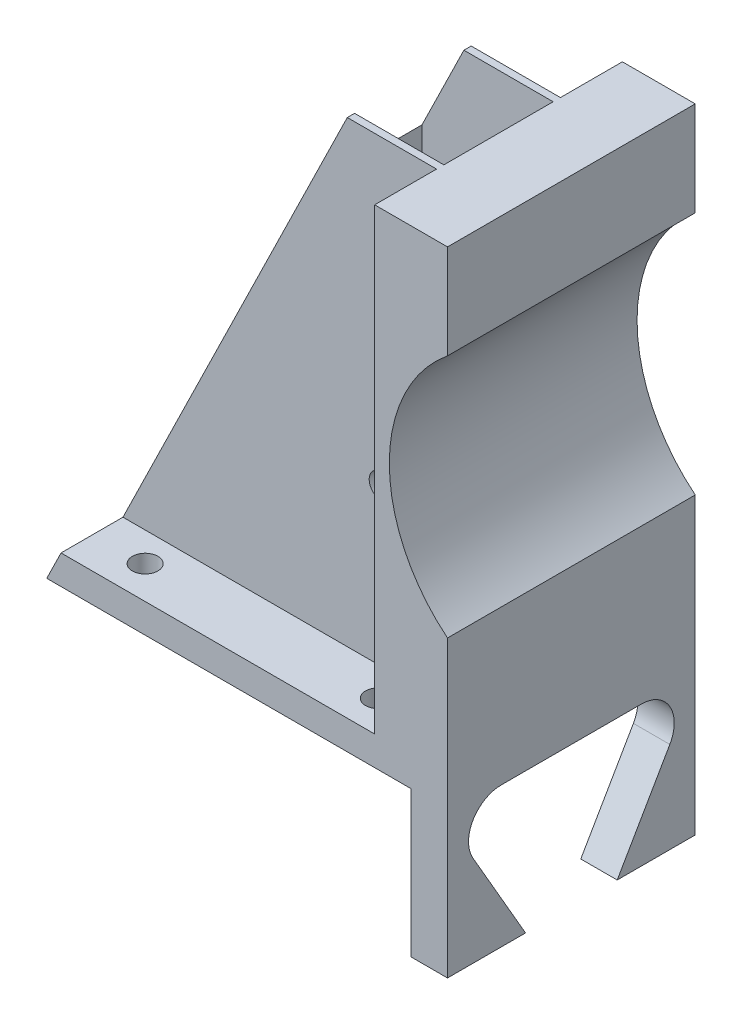
SolidWorks part; units mm, degrees
ref_plane "Front Plane" through (0, 0, 0) normal (0, 0, 1) x (1, 0, 0)
ref_plane "Top Plane" through (0, 0, 0) normal (0, 1, 0) x (1, 0, 0)
ref_plane "Right Plane" through (0, 0, 0) normal (1, 0, 0) x (0, 0, -1)
sketch "Sketch4" plane through (0, 0, 0) normal (0, 0, 1) x (1, 0, 0)
  line L0 (-25, -10) -> (30, -10)
  line L1 (-25, -10) -> (25, -10) construction
  line L2 (-25, -10) -> (-25, 10) construction
  line L3 (-25, 10) -> (25, 10) construction
  line L4 (25, -10) -> (25, 10) construction
  line L5 (-25, -10) -> (25, 10) construction
  line L6 (-25, 10) -> (25, -10) construction
  line L7 (30, -10) -> (30, 30.414)
  line L8 (30, 63.942) -> (30, 76.896)
  line L9 (30, 76.896) -> (7.7472, 76.896)
  line L10 (7.7472, 76.896) -> (-25, 10)
  line L11 (-25, 10) -> (-25, -10)
  arc A0 (30, 63.942) -> (30, 30.414) centre (43.605, 47.178) ccw
  point P0 (0, 0)
  dimension "D3" = 21.59
  dimension "D4" = 12.954
  dimension "D1" = 50
  dimension "D2" = 20
  dimension "D5" = 33.528
  dimension "D6" = 5
extrude "Boss-Extrude2" add sketch "Sketch4" along normal blind 34
sketch "Sketch5" plane through (0, 0, 34) normal (0, 0, 1) x (1, 0, 0)
  line L0 (-23.0419, 14) -> (7.7472, 76.896)
  line L1 (-25, -10) -> (25, -10)
  line L2 (-25, -10) -> (-25, 10)
  line L3 (-25, 10) -> (25, 10)
  line L4 (25, -10) -> (25, 10)
  line L5 (7.7472, 76.896) -> (-25, 10) construction
  line L6 (7.7472, 76.896) -> (20, 76.896)
  line L7 (30, 76.896) -> (7.7472, 76.896) construction
  line L8 (20, 76.896) -> (20, 14)
  line L9 (20, 14) -> (-23.0419, 14)
  dimension "D1" = 50
  dimension "D2" = 20
  dimension "D3" = 4
  dimension "D4" = 45
extrude "Cut-Extrude1" cut sketch "Sketch5" against normal blind 8.5
sketch "Sketch6" plane through (0, 0, 0) normal (0, 0, -1) x (-1, 0, 0)
  line L0 (23.0419, 14) -> (-20, 14)
  line L1 (25, -10) -> (-25, -10)
  line L2 (25, -10) -> (25, 10)
  line L3 (25, 10) -> (-25, 10)
  line L4 (-25, -10) -> (-25, 10)
  line L5 (-7.7472, 76.896) -> (25, 10) construction
  line L6 (-20, 14) -> (-20, 76.896)
  line L7 (-30, 76.896) -> (-7.7472, 76.896) construction
  line L8 (-20, 76.896) -> (-7.7472, 76.896)
  line L9 (-7.7472, 76.896) -> (23.0419, 14)
  dimension "D1" = 50
  dimension "D2" = 20
  dimension "D3" = 45
  dimension "D4" = 4
extrude "Cut-Extrude2" cut sketch "Sketch6" against normal blind 8.5
sketch "Sketch7" plane through (0, 0, 8.5) normal (0, 0, -1) x (-1, 0, 0)
  line L1 (-25, 10) -> (27.0063, 10)
  line L2 (-25, 10) -> (-25, -11.6279)
  line L3 (-25, -11.6279) -> (27.0063, -11.6279)
  line L4 (27.0063, 10) -> (27.0063, -11.6279)
  dimension "D1" = 21.6279
  dimension "D2" = 52.0063
extrude "Cut-Extrude3" cut sketch "Sketch7" against normal through all
sketch "Sketch8" plane through (30, 0, 0) normal (1, 0, 0) x (0, 0, -1)
  line L0 (-26.61, 8) -> (-7.38, 8)
  line L1 (-29.7004, 2.8571) -> (-19.979, -15.4295)
  line L2 (-14.011, -15.4295) -> (-4.2896, 2.8571)
  line L3 (-34, -10) -> (-34, 30.414) construction
  line L5 (0, -10) -> (0, 30.414) construction
  line L6 (-34, -10) -> (0, -10) construction
  line L7 (-34, -10) -> (-34, 10) construction
  line L8 (-34, 10) -> (0, 10) construction
  line L9 (0, -10) -> (0, 10) construction
  line L10 (-26.61, 4.5) -> (-7.38, 4.5) construction
  line L11 (-24.295, -13.8431) -> (-10.3108, -13.8431) construction
  arc A3 (-26.61, 8) -> (-29.7004, 2.8571) centre (-26.61, 4.5) ccw
  arc A4 (-7.38, 8) -> (-4.2896, 2.8571) centre (-7.38, 4.5) cw
  arc A5 (-14.011, -15.4295) -> (-19.979, -15.4295) centre (-16.995, -13.8431) cw
  dimension "D1" = 3.5
  dimension "D2" = 3.5
  dimension "D3" = 3.3794
  dimension "D4" = 19.23
  dimension "D5" = 20.71
  dimension "D6" = 20.71
  dimension "D7" = 7.39
  dimension "D8" = 2
  dimension "D9" = 20
sketch "Sketch9" plane through (30, 0, 0) normal (1, 0, 0) x (0, 0, -1)
  line L0 (-26.615, 8.257) -> (-7.385, 8.257) construction
  line L1 (-4.3541, 3.0067) -> (-13.9691, -13.6433) construction
  line L2 (-29.6459, 3.0067) -> (-20.0309, -13.6433) construction
  line L4 (-34, 30.414) -> (0, 30.414) construction
  line L5 (-26.615, 4.757) -> (-7.385, 4.757) construction
  line L6 (-17, 4.757) -> (-17, -11.893) construction
  line L7 (-34, 10.207) -> (0, 10.207) construction
  line L8 (-34, -10) -> (-34, 30.414) construction
  line L9 (0, -10) -> (0, 30.414) construction
  line L10 (-26.615, 9.257) -> (-7.385, 9.257)
  line L11 (-3.4881, 2.5066) -> (-13.1031, -14.1434)
  line L12 (-30.5119, 2.5066) -> (-20.8969, -14.1434)
  arc A0 (-26.615, 8.257) -> (-29.6459, 3.0067) centre (-26.615, 4.757) ccw construction
  arc A1 (-4.3541, 3.0067) -> (-7.385, 8.257) centre (-7.385, 4.757) ccw construction
  arc A2 (-20.0309, -13.6433) -> (-13.9691, -13.6433) centre (-17, -11.893) ccw construction
  arc A3 (-29.6459, 3.0067) -> (-26.615, 8.257) centre (-26.615, 4.757) ccw construction
  arc A4 (-7.385, 8.257) -> (-4.3541, 3.0067) centre (-7.385, 4.757) ccw construction
  arc A5 (-13.9691, -13.6433) -> (-20.0309, -13.6433) centre (-17, -11.893) ccw construction
  arc A6 (-3.4881, 2.5066) -> (-7.385, 9.257) centre (-7.385, 4.757) ccw
  arc A7 (-20.8969, -14.1434) -> (-13.1031, -14.1434) centre (-17, -11.893) ccw
  arc A8 (-26.615, 9.257) -> (-30.5119, 2.5066) centre (-26.615, 4.757) ccw
  point P21 (-17, 30.414)
  dimension "D1" = 7
  dimension "D2" = 7
  dimension "D3" = 7
  dimension "D4" = 19.23
  dimension "D5" = 16.65
  dimension "D6" = 1.95
  dimension "D7" = 22.1
  dimension "D8" = 1
extrude "Cut-Extrude4" cut sketch "Sketch9" against normal through all
sketch "Sketch10" plane through (0, 10, 0) normal (0, -1, 0) x (1, 0, 0)
  line L0 (25, 23.2896) -> (25, 34) construction
  line L1 (25, 34) -> (-25, 34) construction
  line L3 (-25, 0) -> (25, 0) construction
  line L4 (-25, 34) -> (-25, 0) construction
  circle A0 centre (16, 29.5) radius 1.75
  circle A1 centre (16, 4.5) radius 1.75
  circle A2 centre (-16, 29.5) radius 1.75
  circle A3 centre (-16, 4.5) radius 1.75
  dimension "D3" = 3.5
  dimension "D4" = 3.5
  dimension "D6" = 4.5
  dimension "D7" = 4.5
  dimension "D8" = 4.5
  dimension "D10" = 3.5
  dimension "D11" = 3.5
  dimension "D1" = 25
  dimension "D2" = 9
  dimension "D5" = 4.5
  dimension "D9" = 9
  dimension "D12" = 9
extrude "Cut-Extrude5" cut sketch "Sketch10" against normal blind 10
sketch "Sketch14" plane through (20, 0, 0) normal (-1, 0, 0) x (0, 0, 1)
  line L0 (25.5, 76.896) -> (8.5, 76.896) construction
  line L1 (9.5, 76.896) -> (24.5, 76.896)
  line L2 (9.5, 76.896) -> (9.5, 39.896)
  line L3 (9.5, 39.896) -> (24.5, 39.896)
  line L4 (24.5, 76.896) -> (24.5, 39.896)
  line L5 (8.5, 76.896) -> (8.5, 14) construction
  dimension "D1" = 15
  dimension "D2" = 1
  dimension "D3" = 37
extrude "Cut-Extrude8" cut sketch "Sketch14" along normal blind 18
sketch "Sketch15" plane through (0, 39.896, 0) normal (0, 1, 0) x (1, 0, 0)
  line L1 (2, -9.5) -> (20, -9.5)
  line L2 (2, -9.5) -> (2, -24.5)
  line L3 (2, -24.5) -> (20, -24.5)
  line L4 (20, -9.5) -> (20, -24.5)
extrude "Cut-Extrude9" cut sketch "Sketch15" against normal blind 9
sketch "Sketch16" plane through (20, 0, 0) normal (-1, 0, 0) x (0, 0, 1)
  line L1 (10.5, 39.896) -> (23.5, 39.896)
  line L2 (10.5, 39.896) -> (10.5, 30.896)
  line L3 (10.5, 30.896) -> (23.5, 30.896)
  line L4 (23.5, 39.896) -> (23.5, 30.896)
  line L5 (24.5, 76.896) -> (9.5, 76.896) construction
  line L6 (8.5, 76.896) -> (8.5, 14) construction
  dimension "D1" = 46
  dimension "D2" = 37
  dimension "D3" = 13
  dimension "D4" = 2
extrude "Cut-Extrude10" cut sketch "Sketch16" along normal through all
sketch "Sketch17" plane through (0, 0, 25.5) normal (0, 0, 1) x (1, 0, 0)
  line L0 (2, 30.896) -> (20, 30.896) construction
  line L1 (20, 14) -> (20, 76.896) construction
  circle A0 centre (12.5, 35.396) radius 1.75
  dimension "D1" = 3.5
  dimension "D2" = 4.5
  dimension "D3" = 7.5
extrude "Cut-Extrude11" cut sketch "Sketch17" against normal through all
equation "\"D1@Sketch9\"=3.5*2mm"
